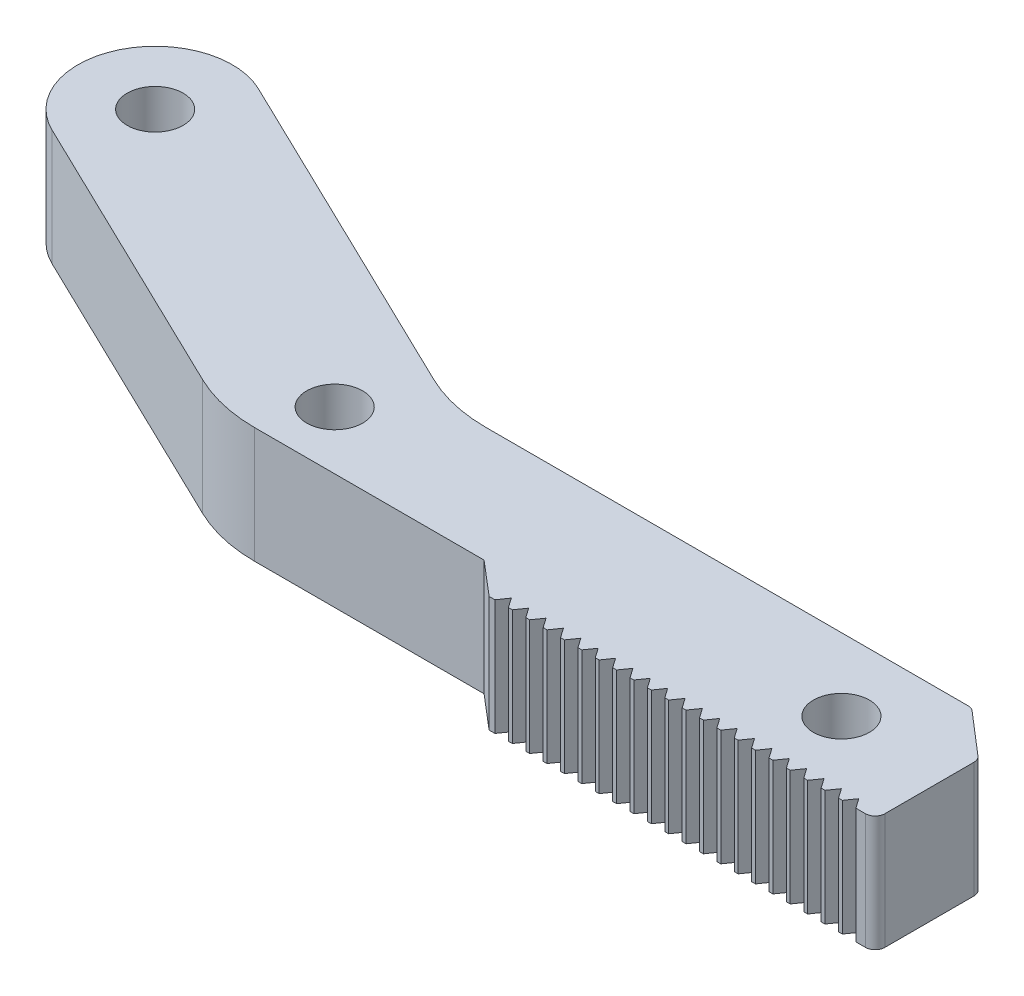
SolidWorks part; units mm, degrees
ref_plane "Alzado" through (0, 0, 0) normal (0, 0, 1) x (1, 0, 0)
ref_plane "Planta" through (0, 0, 0) normal (0, 1, 0) x (1, 0, 0)
ref_plane "Vista lateral" through (0, 0, 0) normal (1, 0, 0) x (0, 0, -1)
sketch "Croquis base" plane through (0, 0, 0) normal (0, 1, 0) x (1, 0, 0)
  line L0 (16.2564, 0) -> (-16.2436, 0) construction
  line L1 (-5.5056, -3) -> (-16.2436, -3)
  line L2 (16.2564, -3) -> (16.2564, 0.85)
  line L3 (13.7564, 3) -> (-13.2589, 3)
  line L5 (-16.2436, 0) -> (-34.25, 8.7046) construction
  line L6 (-16.2436, 0) -> (-34.25, 0) construction
  line L7 (-32.5091, 12.3059) -> (-13.2589, 3)
  line L8 (-35.9909, 5.1033) -> (-19.2283, -3)
  line L9 (-16.2436, -3) -> (-19.2283, -3)
  line L10 (16.2564, -3) -> (16.2564, -4.5)
  line L11 (16.2564, -4.5) -> (-3.7436, -4.5) construction
  line L12 (-3.7436, -4.5) -> (-3.7436, -3) construction
  line L13 (15.2564, -4.5) -> (14.9064, -4)
  line L14 (14.9064, -4) -> (14.5564, -4.5)
  line L15 (15.2564, -4.5) -> (16.2564, -4.5)
  line L16 (14.5564, -4.5) -> (14.3564, -4.5)
  line L17 (14.0064, -4) -> (13.6564, -4.5)
  line L18 (13.6564, -4.5) -> (13.4564, -4.5)
  line L19 (14.3564, -4.5) -> (14.0064, -4)
  line L20 (13.1064, -4) -> (12.7564, -4.5)
  line L21 (12.7564, -4.5) -> (12.5564, -4.5)
  line L22 (13.4564, -4.5) -> (13.1064, -4)
  line L23 (12.2064, -4) -> (11.8564, -4.5)
  line L24 (11.8564, -4.5) -> (11.6564, -4.5)
  line L25 (12.5564, -4.5) -> (12.2064, -4)
  line L26 (11.3064, -4) -> (10.9564, -4.5)
  line L27 (10.9564, -4.5) -> (10.7564, -4.5)
  line L28 (11.6564, -4.5) -> (11.3064, -4)
  line L29 (10.4064, -4) -> (10.0564, -4.5)
  line L30 (10.0564, -4.5) -> (9.8564, -4.5)
  line L31 (10.7564, -4.5) -> (10.4064, -4)
  line L32 (9.5064, -4) -> (9.1564, -4.5)
  line L33 (9.1564, -4.5) -> (8.9564, -4.5)
  line L34 (9.8564, -4.5) -> (9.5064, -4)
  line L35 (8.6064, -4) -> (8.2564, -4.5)
  line L36 (8.2564, -4.5) -> (8.0564, -4.5)
  line L37 (8.9564, -4.5) -> (8.6064, -4)
  line L38 (7.7064, -4) -> (7.3564, -4.5)
  line L39 (7.3564, -4.5) -> (7.1564, -4.5)
  line L40 (8.0564, -4.5) -> (7.7064, -4)
  line L41 (6.8064, -4) -> (6.4564, -4.5)
  line L42 (6.4564, -4.5) -> (6.2564, -4.5)
  line L43 (7.1564, -4.5) -> (6.8064, -4)
  line L44 (5.9064, -4) -> (5.5564, -4.5)
  line L45 (5.5564, -4.5) -> (5.3564, -4.5)
  line L46 (6.2564, -4.5) -> (5.9064, -4)
  line L47 (5.0064, -4) -> (4.6564, -4.5)
  line L48 (4.6564, -4.5) -> (4.4564, -4.5)
  line L49 (5.3564, -4.5) -> (5.0064, -4)
  line L50 (4.1064, -4) -> (3.7564, -4.5)
  line L51 (3.7564, -4.5) -> (3.5564, -4.5)
  line L52 (4.4564, -4.5) -> (4.1064, -4)
  line L53 (3.2064, -4) -> (2.8564, -4.5)
  line L54 (2.8564, -4.5) -> (2.6564, -4.5)
  line L55 (3.5564, -4.5) -> (3.2064, -4)
  line L56 (2.3064, -4) -> (1.9564, -4.5)
  line L57 (1.9564, -4.5) -> (1.7564, -4.5)
  line L58 (2.6564, -4.5) -> (2.3064, -4)
  line L59 (1.4064, -4) -> (1.0564, -4.5)
  line L60 (1.0564, -4.5) -> (0.8564, -4.5)
  line L61 (1.7564, -4.5) -> (1.4064, -4)
  line L62 (0.5064, -4) -> (0.1564, -4.5)
  line L63 (0.1564, -4.5) -> (-0.0436, -4.5)
  line L64 (0.8564, -4.5) -> (0.5064, -4)
  line L65 (-0.3936, -4) -> (-0.7436, -4.5)
  line L66 (-0.7436, -4.5) -> (-0.9436, -4.5)
  line L67 (-0.0436, -4.5) -> (-0.3936, -4)
  line L68 (-1.2936, -4) -> (-1.6436, -4.5)
  line L69 (-1.6436, -4.5) -> (-1.8436, -4.5)
  line L70 (-0.9436, -4.5) -> (-1.2936, -4)
  line L71 (-2.1936, -4) -> (-2.5436, -4.5)
  line L72 (-2.5436, -4.5) -> (-2.7436, -4.5)
  line L73 (-1.8436, -4.5) -> (-2.1936, -4)
  line L74 (-3.0936, -4) -> (-3.4436, -4.5)
  line L75 (-3.4436, -4.5) -> (-3.6436, -4.5)
  line L76 (-2.7436, -4.5) -> (-3.0936, -4)
  line L77 (14.9064, -4) -> (14.0064, -4) construction
  line L78 (-3.6436, -4.5) -> (-3.7436, -4.5)
  line L79 (-3.7436, -4.5) -> (-5.5056, -3)
  line L80 (16.2564, -4.5) -> (16.2564, -3)
  line L81 (-5.5056, -3) -> (16.2564, -3) construction
  line L82 (13.7564, 3) -> (16.2564, 0.85)
  arc A0 (-32.5091, 12.3059) -> (-35.9909, 5.1033) centre (-34.25, 8.7046) ccw
  circle A1 centre (-34.25, 8.7046) radius 1.45
  circle A2 centre (-16.2436, 0) radius 1.45
  circle A3 centre (10.7564, -0.75) radius 1.45
  point P0 (0, 0)
  dimension "D8" = 21.3815
  dimension "D9" = 4
  dimension "D19" = 2.9
  dimension "D1" = 6
  dimension "D2" = 32.5
  dimension "D3" = 20
  dimension "D4" = 18.0064
  dimension "D5" = 25.8
  dimension "D6" = 8
  dimension "D7" = 4
  dimension "D10" = 1.5
  dimension "D11" = 20
  dimension "D12" = 1
  dimension "D13" = 0.7
  dimension "D14" = 0.2
  dimension "D15" = 0.5
  dimension "D17" = 0.9
  dimension "D18" = 1.762
  dimension "D20" = 5.5
  dimension "D21" = 2.25
  dimension "D22" = 2.5
  dimension "D23" = 2.15
  dimension "D16" = 21
extrude "Saliente-Extruir1" add sketch "Croquis base" along normal blind 6 contours L7 A0 L8 L9 L1 L79 L78 L75 L74 L76 L72 L71 L73 L69 L68 L70 L66 L65 L67 L63 L62 L64 L60 L59 L61 L57 L56 L58 L54 L53 L55 L51 L50 L52 L48 L47 L49 L45 L44 L46 L42 L41 L43 L39 L38 L40 L36 L35 L37 L33 L32
fillet "Redondeo2" radius 8 2 edges at (-13.2589, 3, -3) (-19.2283, 3, 3)
fillet "Redondeo1" radius 0.5 3 edges at (16.2564, 3, 4.5) (13.7564, 3, -3) (16.2564, 3, -0.85)
